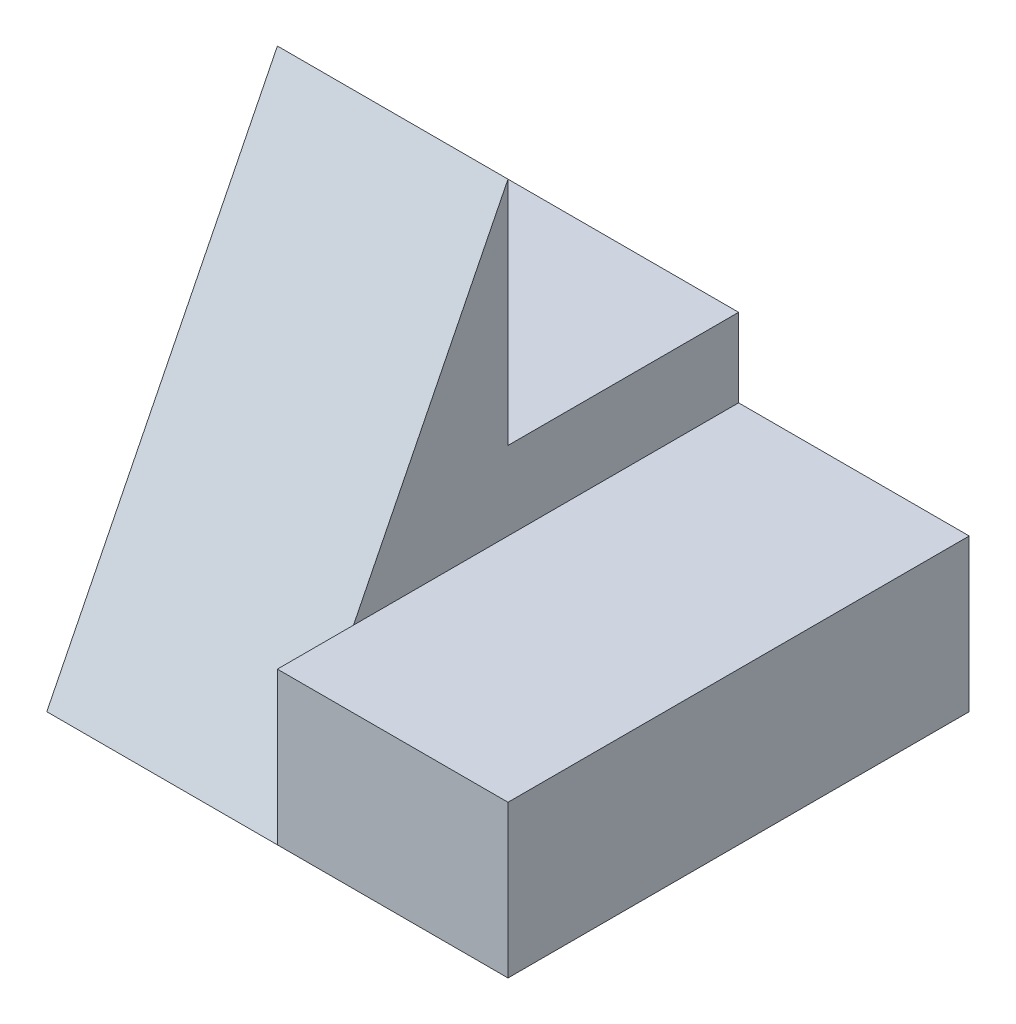
SolidWorks part; units mm, degrees
ref_plane "Front Plane" through (0, 0, 0) normal (0, 0, 1) x (1, 0, 0)
ref_plane "Top Plane" through (0, 0, 0) normal (0, 1, 0) x (1, 0, 0)
ref_plane "Right Plane" through (0, 0, 0) normal (1, 0, 0) x (0, 0, -1)
sketch "Sketch1" plane through (0, 0, 0) normal (0, 1, 0) x (1, 0, 0)
  line L1 (0, 0) -> (1, 0)
  line L2 (0, 0) -> (0, 1)
  line L3 (0, 1) -> (1, 1)
  line L4 (1, 0) -> (1, 1)
  dimension "D1" = 1
  dimension "D2" = 1
extrude "Boss-Extrude1" add sketch "Sketch1" along normal blind 1
sketch "Sketch2" plane through (1, 0, 0) normal (1, 0, 0) x (0, 0, -1)
  line L0 (0, 0.33) -> (1, 0.33)
  line L1 (0, 1) -> (0, 0) construction
  line L2 (1, 1) -> (1, 0) construction
  line L3 (0, 0) -> (1, 0) construction
  dimension "D1" = 0.33
extrude "Cut-Extrude1" cut sketch "Sketch2" against normal blind 0.5 and the other way through all
sketch "Sketch3" plane through (0, 0, 0) normal (-1, 0, 0) x (0, 0, 1)
  line L0 (0, 0) -> (-0.5, 1)
  line L1 (-1, 1) -> (0, 1) construction
  line L2 (-0.5, 1) -> (-0.5, 0.5)
  line L3 (-0.5, 0.5) -> (-1, 0.5)
  line L4 (-1, 1) -> (-1, 0) construction
  point P5 (0, 0)
  point P10 (0, 0)
  point P11 (0, 0)
  point P12 (0, 0)
extrude "Cut-Extrude2" cut sketch "Sketch3" against normal blind 0.5 and the other way through all flip side to cut
